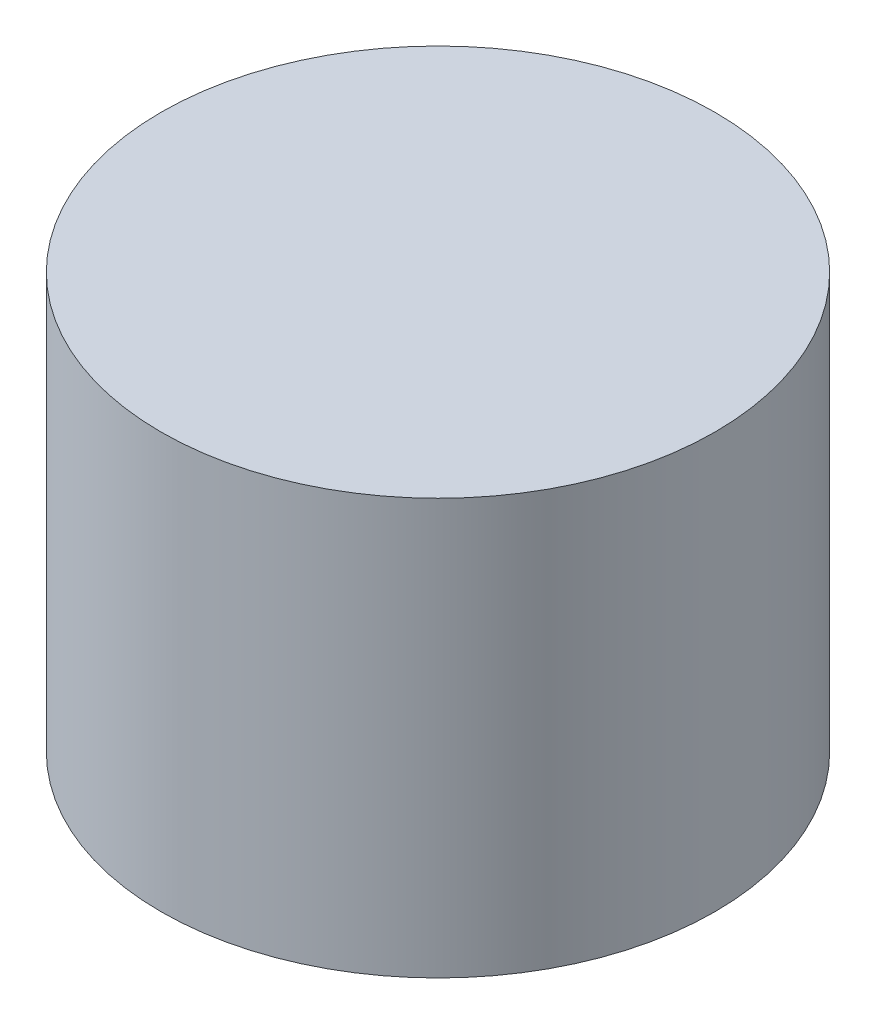
SolidWorks part; units mm, degrees
ref_plane "前视基准面" through (0, 0, 0) normal (0, 0, 1) x (1, 0, 0)
ref_plane "上视基准面" through (0, 0, 0) normal (0, 1, 0) x (1, 0, 0)
ref_plane "右视基准面" through (0, 0, 0) normal (1, 0, 0) x (0, 0, -1)
sketch "草图1" plane through (0, 0, 0) normal (0, 1, 0) x (1, 0, 0)
  circle A0 centre (0, 0) radius 30
  dimension "D1" = 60
extrude "凸台-拉伸1" add sketch "草图1" along normal blind 45
